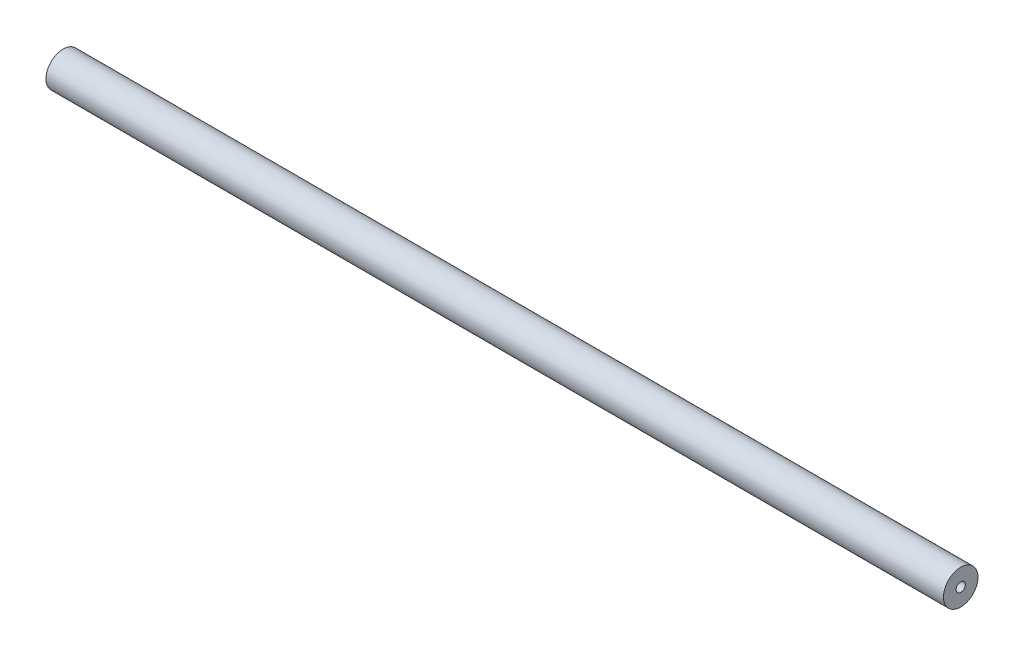
SolidWorks part; units mm, degrees
material "AISI 1045 Steel, cold drawn"
ref_plane "Front Plane" through (0, 0, 0) normal (0, 0, 1) x (1, 0, 0)
ref_plane "Top Plane" through (0, 0, 0) normal (0, 1, 0) x (1, 0, 0)
ref_plane "Right Plane" through (0, 0, 0) normal (1, 0, 0) x (0, 0, -1)
sketch "Sketch1" plane through (0, 0, 0) normal (1, 0, 0) x (0, 0, -1)
  circle A0 centre (0, 0) radius 9.525
  dimension "D1" = 19.05
extrude "Boss-Extrude1" add sketch "Sketch1" against normal blind 495.3
hole_wizard "1/4-20 Tapped Hole1" positions "Sketch3" profile "Sketch4" tap size "1/4-20" standard "ANSI Inch"
sketch "Sketch3" plane through (0, 0, 0) normal (1, 0, 0) x (0, 0, -1)
  point P0 (0, 0)
sketch "Sketch4" plane through (0, 0, 0) normal (0, 1, 0) x (0, 0, -1)
  line L0 (0, 0) -> (0, 18.0438)
  line L1 (0, 18.0438) -> (2.5527, 16.51)
  line L2 (2.5527, 16.51) -> (2.5527, 0)
  line L5 (2.5527, 0) -> (0, 0)
  line L10 (0, 18.0438) -> (-2.5527, 16.51) construction
  line L11 (0, -6.35) -> (0, 107.95) construction
  dimension "Tap Drill Dia." = 5.1054
  dimension "Tap Drill Depth" = 16.51
  dimension "Drill Angle" = 118
cosmetic thread "Hole Thread1"
hole_wizard "1/4-20 Tapped Hole2" positions "Sketch5" profile "Sketch6" tap size "1/4-20" standard "ANSI Inch"
sketch "Sketch5" plane through (-495.3, 0, 0) normal (-1, 0, 0) x (0, 0, 1)
  point P0 (0, 0)
sketch "Sketch6" plane through (-495.3, 0, 0) normal (0, 1, 0) x (0, 0, 1)
  line L0 (0, 0) -> (0, 18.0438)
  line L1 (0, 18.0438) -> (2.5527, 16.51)
  line L2 (2.5527, 16.51) -> (2.5527, 0)
  line L5 (2.5527, 0) -> (0, 0)
  line L10 (0, 18.0438) -> (-2.5527, 16.51) construction
  line L11 (0, -6.35) -> (0, 107.95) construction
  dimension "Tap Drill Dia." = 5.1054
  dimension "Tap Drill Depth" = 16.51
  dimension "Drill Angle" = 118
cosmetic thread "Hole Thread2" parameters "D1"=12.7, "D2"=6.35
